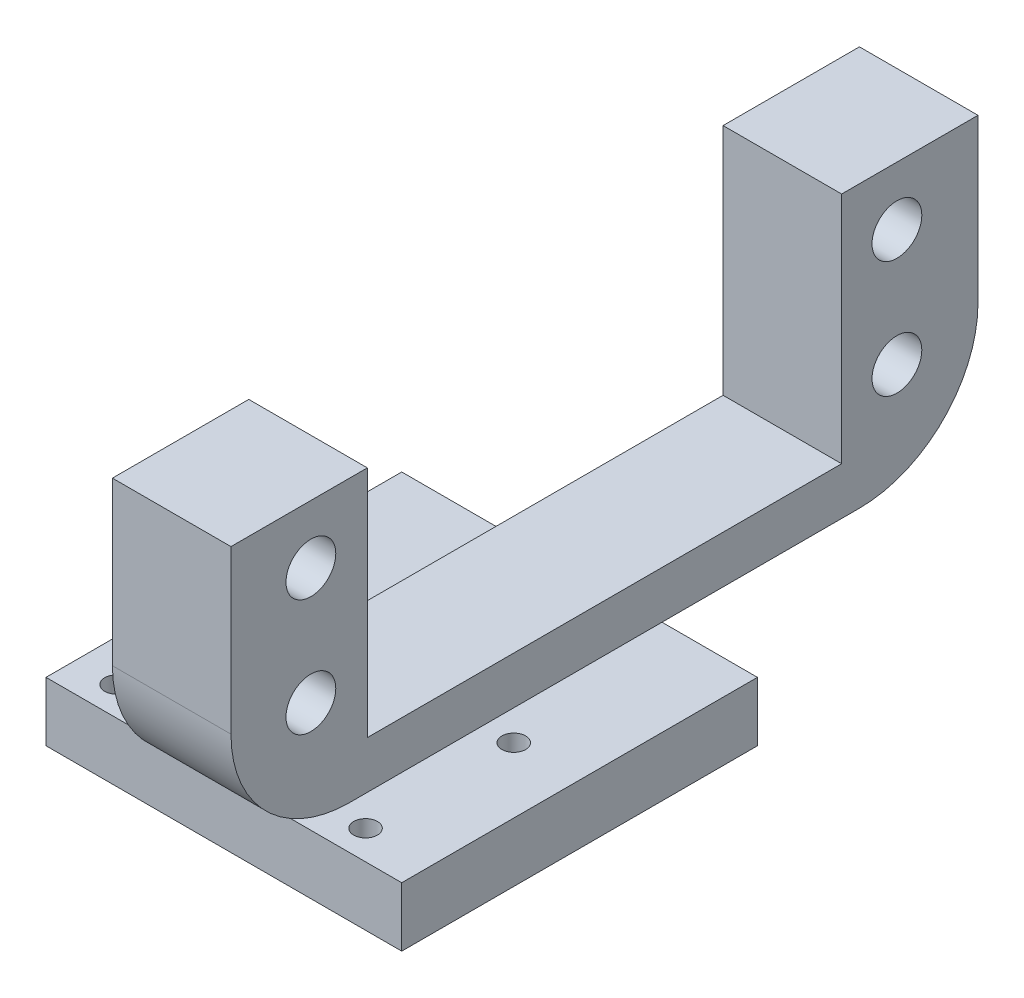
SolidWorks part; units mm, degrees
material "Aluminium 1050"
ref_plane "Front Plane" through (0, 0, 0) normal (0, 0, 1) x (1, 0, 0)
ref_plane "Top Plane" through (0, 0, 0) normal (0, 1, 0) x (1, 0, 0)
ref_plane "Right Plane" through (0, 0, 0) normal (1, 0, 0) x (0, 0, -1)
sketch "Sketch2" plane through (0, 0, 0) normal (1, 0, 0) x (0, 0, -1)
  line L0 (0, 0) -> (63, 0)
  line L6 (63, 0) -> (63, 23.7)
  line L7 (63, 23.7) -> (51.5, 23.7)
  line L8 (51.5, 23.7) -> (51.5, 4)
  line L9 (51.5, 4) -> (11.5, 4)
  line L10 (31.5, 0) -> (31.5, 23.7) construction
  line L11 (0, 0) -> (0, 23.7)
  line L12 (0, 23.7) -> (11.5, 23.7)
  line L13 (11.5, 23.7) -> (11.5, 4)
  point P12 (31.5, 4)
  dimension "D1" = 11.5
  dimension "D2" = 40
  dimension "D3" = 11.5
  dimension "D4" = 19.7
  dimension "D5" = 4
extrude "Boss-Extrude1" add sketch "Sketch2" along normal blind 10
sketch "Sketch3" plane through (10, 0, 0) normal (1, 0, 0) x (0, 0, -1)
  circle A8 centre (6.7389, 18.775) radius 2.1
  circle A9 centre (56.1611, 18.775) radius 2.1
  circle A10 centre (56.1611, 8.925) radius 2.1
  circle A11 centre (6.7389, 8.925) radius 2.1
extrude "Cut-Extrude2" cut sketch "Sketch3" against normal up to surface (10 mm away) up to face at (0, 12.85, -31.5)
fillet "Fillet1" radius 10 2 edges at (5, 0, -63) (5, 0, 0)
sketch "Sketch4" plane through (0, 0, 0) normal (0, -1, 0) x (1, 0, 0)
  line L0 (18.05, -21.35) -> (-11.95, -21.35) construction
  line L3 (18.05, -6.35) -> (-11.95, -6.35)
  line L4 (-11.95, -6.35) -> (-11.95, -36.35)
  line L9 (18.05, -36.35) -> (-11.95, -36.35)
  line L14 (18.05, -6.35) -> (18.05, -36.35)
  line L17 (3.05, -6.35) -> (3.05, -36.35) construction
extrude "Boss-Extrude2" add sketch "Sketch4" along normal blind 5
sketch "Sketch6" plane through (0, -5, 0) normal (0, -1, 0) x (1, 0, 0)
  circle A0 centre (-8.45, -8.8) radius 1
  circle A1 centre (12.55, -8.8) radius 1
  circle A2 centre (12.55, -21.3) radius 1
  circle A3 centre (-8.45, -21.3) radius 1
  dimension "D1" = 2
  dimension "D2" = 2
  dimension "D3" = 2
  dimension "D4" = 2
extrude "Cut-Extrude3" cut sketch "Sketch6" against normal up to surface (5 mm away) up to face at (4.025, 0, -22.2625)
